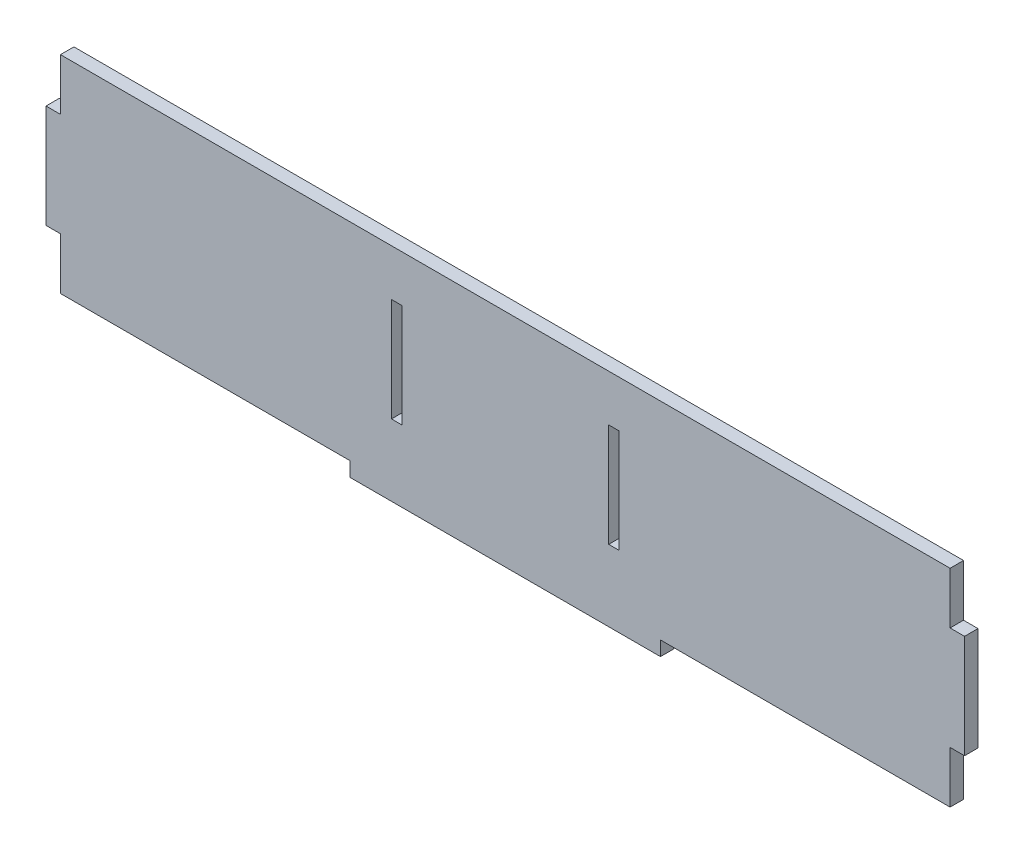
SolidWorks part; units mm, degrees
ref_plane "Front Plane" through (0, 0, 0) normal (0, 0, 1) x (1, 0, 0)
ref_plane "Top Plane" through (0, 0, 0) normal (0, 1, 0) x (1, 0, 0)
ref_plane "Right Plane" through (0, 0, 0) normal (1, 0, 0) x (0, 0, -1)
sketch "Sketch1" plane through (0, 0, 0) normal (0, 0, 1) x (1, 0, 0)
  line L1 (-43, 10) -> (43, 10)
  line L2 (-43, 10) -> (-43, -10)
  line L3 (-43, -10) -> (43, -10)
  line L4 (43, 10) -> (43, -10)
  line L5 (-43, 10) -> (43, -10) construction
  line L6 (-43, -10) -> (43, 10) construction
  point P0 (0, 0)
  dimension "D1" = 20
  dimension "D2" = 86
extrude "Boss-Extrude1" add sketch "Sketch1" along normal blind 1.3
sketch "Sketch2" plane through (0, 0, 1.3) normal (0, 0, 1) x (1, 0, 0)
  line L0 (-43, -10) -> (43, -10) construction
  line L1 (-15, -10) -> (15, -10)
  line L2 (-15, -10) -> (-15, -11.4)
  line L3 (-15, -11.4) -> (15, -11.4)
  line L4 (15, -10) -> (15, -11.4)
  line L5 (0, -0.715) -> (0, 0.715) construction
  line L6 (-43, 10) -> (-43, -10) construction
  line L7 (-43, 5) -> (-44.4, 5)
  line L8 (-43, 5) -> (-43, -5)
  line L9 (-43, -5) -> (-44.4, -5)
  line L10 (-44.4, 5) -> (-44.4, -5)
  line L11 (43, -10) -> (43, 10) construction
  line L12 (43, 5) -> (44.4, 5)
  line L13 (43, 5) -> (43, -5)
  line L14 (43, -5) -> (44.4, -5)
  line L15 (44.4, 5) -> (44.4, -5)
  dimension "D1" = 1.4
  dimension "D2" = 30
  dimension "D3" = 15
  dimension "D4" = 1.4
  dimension "D5" = 1.4
  dimension "D6" = 10
  dimension "D7" = 5
  dimension "D8" = 5
  dimension "D9" = 10
extrude "Boss-Extrude2" add sketch "Sketch2" against normal blind 1.3
sketch "Sketch3" plane through (0, 0, 1.3) normal (0, 0, 1) x (1, 0, 0)
  line L0 (-43, -10) -> (-15, -10) construction
  line L1 (-11, 5.5) -> (-10, 5.5)
  line L2 (-11, 5.5) -> (-11, -4.5)
  line L3 (-11, -4.5) -> (-10, -4.5)
  line L4 (-10, 5.5) -> (-10, -4.5)
  line L5 (10, 5.5) -> (11, 5.5)
  line L6 (10, 5.5) -> (10, -4.5)
  line L7 (10, -4.5) -> (11, -4.5)
  line L8 (11, 5.5) -> (11, -4.5)
  line L9 (15, -10) -> (43, -10) construction
  line L10 (0, -0.715) -> (0, 0.715) construction
  dimension "D1" = 5.5
  dimension "D2" = 5.5
  dimension "D3" = 1
  dimension "D4" = 1
  dimension "D5" = 10
  dimension "D6" = 10
  dimension "D7" = 10
  dimension "D8" = 10
extrude "Cut-Extrude1" cut sketch "Sketch3" against normal through all
